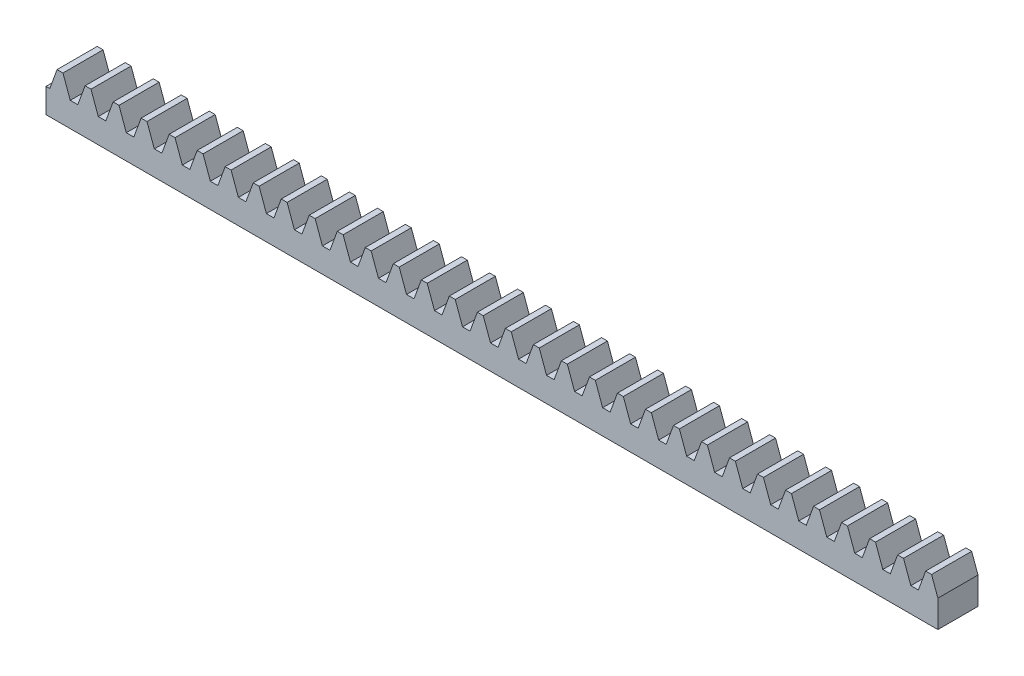
SolidWorks part; units mm, degrees
extrude "Blank" add sketch "BlankSke" against normal blind 45
sketch "BlankSke" plane through (0, 0, 0) normal (0, 0, 1) x (1, 0, 0)
  line L1 (0, 0) -> (1000, 0)
  line L2 (0, 0) -> (0, 50)
  line L3 (0, 50) -> (1000, 50)
  line L4 (1000, 0) -> (1000, 50)
  dimension "Length" = 1000
  dimension "Blank_height" = 50
ref_plane "Plane1" through (0, 0, 0) normal (0, 0, 1) x (1, 0, 0)
ref_plane "Plane2" through (0, 0, 0) normal (0, 1, 0) x (1, 0, 0)
ref_plane "Plane3" through (0, 0, 0) normal (1, 0, 0) x (0, 0, -1)
sketch "HoldingSke" plane through (0, 0, 0) normal (0, 1, 0) x (1, 0, 0)
  line L0 (0, 0) -> (0.0139, 0.099)
  line L1 (-15, 0) -> (100, 0) construction
  line L2 (0, 0) -> (-2.1039, 2.3779)
  line L3 (0, 0) -> (-11.863, 4.5341)
  line L4 (0, 0) -> (7.2428, 4.7035)
  line L5 (0, 0) -> (-23.7986, -8.8762)
  line L6 (0, 0) -> (-10.5278, -7.1032)
  line L9 (-71.009, 38.7566) -> (868.6837, 380.7768)
  line L10 (-76.2, 12.3779) -> (-36.2, 12.3779)
  line L11 (0, 0) -> (-45, 0)
  line L12 (-76.2, 101.6) -> (-75.896, 101.6)
  line L13 (24.9733, 27.94) -> (52.9518, 28.4284)
  line L14 (24.9733, 27.94) -> (24.9743, 27.94)
  line L15 (24.9733, 27.94) -> (100.4006, 29.5858)
  circle A0 centre (0, 0) radius 19.05
  circle A1 centre (0, 0) radius 20
  circle A2 centre (0, 0) radius 12.7
  dimension "MPH" = 40
  dimension "Diameter" = 38.1
  dimension "Num_teeth" = 33
  dimension "Pitch" = 0.1
  dimension "Show_teeth" = 998
  dimension "Thickness" = 12.7
  dimension "Ap" = 20
  dimension "Pitch_height" = 40
  dimension "Width" = 45
  dimension "Backlash" = 0.304
  dimension "Addendum_fac" = 1
  dimension "Dedendum_fac" = 1.25
  dimension "Clearance_fac" = 0.25
  dimension "Dedendum_add" = 0.001
  dimension "Length" = 1000
  dimension "Module" = 10
sketch "TooCutSkeIll" plane through (0, 0, 0) normal (0, 0, 1) x (1, 0, 0)
  line L0 (-12.3099, 49.7368) -> (-4.8153, 29.1456)
  line L1 (-2.4651, 27.5) -> (2.4651, 27.5)
  line L2 (4.8153, 29.1456) -> (12.3099, 49.7368)
  line L3 (1000, 50) -> (0, 50) construction
  line L4 (0, 0) -> (0, 64.897) construction
  line L5 (-13.208, 40) -> (12.954, 40) construction
  line L6 (0, 0) -> (1000, 0) construction
  line L7 (8.766, 40) -> (8.766, 48.7463) construction
  line L8 (-8.766, 40) -> (-8.766, 48.7463) construction
  line L9 (12.6858, 50) -> (12.6858, 50.0254)
  line L10 (-12.6858, 50) -> (-12.6858, 50.0254)
  line L11 (-12.6858, 50.0254) -> (12.6858, 50.0254)
  arc A0 (2.4651, 27.5) -> (4.8153, 29.1456) centre (2.4651, 30.001) ccw
  arc A1 (-4.8153, 29.1456) -> (-2.4651, 27.5) centre (-2.4651, 30.001) ccw
  arc A2 (12.6858, 50) -> (12.3099, 49.7368) centre (12.6858, 49.6) ccw
  arc A3 (-12.3099, 49.7368) -> (-12.6858, 50) centre (-12.6858, 49.6) ccw
  dimension "Pitch_height" = 40
  dimension "Addendum_plus" = 10.0254
  dimension "Pressure_angle" = 20
  dimension "Gap_width" = 17.532
  dimension "Dedendum" = 12.5
extrude "ToothCutIll" [suppressed] cut sketch "TooCutSkeIll" against normal through all
sketch "TooCutSkeSim" plane through (0, 0, 0) normal (0, 0, 1) x (1, 0, 0)
  line L0 (4.2164, 27.5) -> (-4.2164, 27.5)
  line L1 (12.4149, 50.0254) -> (4.2164, 27.5)
  line L2 (0, 17.4625) -> (0, 53.467) construction
  line L3 (12.4149, 50.0254) -> (-12.4149, 50.0254)
  line L6 (-12.4149, 50.0254) -> (-4.2164, 27.5)
  line L9 (-8.766, 40) -> (8.766, 40) construction
  line L10 (0, 0) -> (1000, 0) construction
  line L11 (8.766, 40) -> (8.766, 53.467) construction
  line L12 (-8.766, 40) -> (-8.766, 53.467) construction
  dimension "Pitch_height" = 40
  dimension "Addendum_plus" = 10.0254
  dimension "Pressure_angle" = 20
  dimension "Gap_width" = 17.532
  dimension "Dedendum" = 12.5
extrude "ToothCutSim" cut sketch "TooCutSkeSim" against normal through all
pattern_linear "TeethCuts" count 32 spacing 31.4159 along (1, 0, 0) of "ToothCutIll", "ToothCutSim"
equation "' \"Module@HoldingSke\" = 6.35"
equation "' \"Num_teeth@HoldingSke\" = 12"
equation "' \"Ap@HoldingSke\" =  20"
equation "' \"Ap@HoldingSke\" = 20"
equation "' \"Width@HoldingSke\" = 0.25 * 25.4"
equation "' \"Show_teeth@HoldingSke\" = 500"
equation "' \"Backlash@HoldingSke\" = 0.009 * 25.4"
equation "' \"Addendum_fac@HoldingSke\" = 1.0"
equation "' \"Dedendum_fac@HoldingSke\" = 1.25"
equation "' \"Dedendum_add@HoldingSke\" = 0.00005 * 25.4"
equation "' \"Clearance_fac@HoldingSke\" = 0.25"
equation "' \"Pitch_height@HoldingSke\" = 1 * 25.4"
equation "' \"Length@HoldingSke\" = 4.71 * 25.4"
equation "\"Pitch@HoldingSke\" = 1 / \"Module@HoldingSke\""
equation "\"MPH@HoldingSke\" = \"Dedendum_fac@HoldingSke\" / \"Pitch@HoldingSke\" + 2 * \"Dedendum_add@HoldingSke\" + 0.002 * 25.4"
equation "\"MPH@HoldingSke\" = ((sgn( \"MPH@HoldingSke\" - \"Pitch_height@HoldingSke\")+1)*( \"MPH@HoldingSke\" - \"Pitch_height@HoldingSke\"))/2 + \"Pitch_height@HoldingSke\""
equation "\"Blank_height@BlankSke\" = \"Pitch_height@HoldingSke\" + \"Addendum_fac@HoldingSke\"  / \"Pitch@HoldingSke\" "
equation "\"Length@BlankSke\" =  \"Length@HoldingSke\""
equation "\"Face_width@Blank\" = \"Width@HoldingSke\""
equation "\"Pressure_angle@TooCutSkeIll\" = \"Ap@HoldingSke\""
equation "\"Addendum_plus@TooCutSkeIll\" =  \"Addendum_fac@HoldingSke\"  / \"Pitch@HoldingSke\" + 0.001 *25.4"
equation "\"Dedendum@TooCutSkeIll\" = \"Dedendum_fac@HoldingSke\"  / \"Pitch@HoldingSke\""
equation "\"Pitch_height@TooCutSkeIll\" =  \"MPH@HoldingSke\""
equation "\"Gap_width@TooCutSkeIll\" = 3.14159265 / 2 / \"Pitch@HoldingSke\" + 6 * \"Backlash@HoldingSke\""
equation "\"Pressure_angle@TooCutSkeSim\" = \"Ap@HoldingSke\""
equation "\"Addendum_plus@TooCutSkeSim\" =  \"Addendum_fac@HoldingSke\"  / \"Pitch@HoldingSke\" + 0.001 * 25.4"
equation "\"Dedendum@TooCutSkeSim\" = \"Dedendum_fac@HoldingSke\"  / \"Pitch@HoldingSke\""
equation "\"Pitch_height@TooCutSkeSim\" =  \"MPH@HoldingSke\""
equation "\"Gap_width@TooCutSkeSim\" = 3.14159265 / 2 / \"Pitch@HoldingSke\" + 6 * \"Backlash@HoldingSke\""
equation "\"Root_fillet@TooCutSkeIll\" = \"Clearance_fac@HoldingSke\" / \"Pitch@HoldingSke\" + \"Dedendum_add@HoldingSke\""
equation "\"Break_rad@TooCutSkeIll\" = 0.02 / \"Pitch@HoldingSke\" * 2"
equation "\"Linear_pitch@TeethCuts\" = 3.14159265 / \"Pitch@HoldingSke\""
equation "\"Num_teeth@HoldingSke\" = int( ( \"Length@HoldingSke\" + 0 ) / (3.14159265 / \"Pitch@HoldingSke\")) + 0.9999  + 1"
equation " \"Num_teeth@TeethCuts\" = int( \"Show_teeth@HoldingSke\" ) + 1"
equation " \"Num_teeth@TeethCuts\" = ((sgn( \"Num_teeth@TeethCuts\" - \"Num_teeth@HoldingSke\" )-1)*( \"Num_teeth@TeethCuts\" - \"Num_teeth@HoldingSke\" ))/-2+ \"Num_teeth@HoldingSke\""
equation " \"Num_teeth@TeethCuts\" = ((sgn( \"Num_teeth@TeethCuts\" - 2.0)+1)*( \"Num_teeth@TeethCuts\" - 2.0))/2 +2.0"
